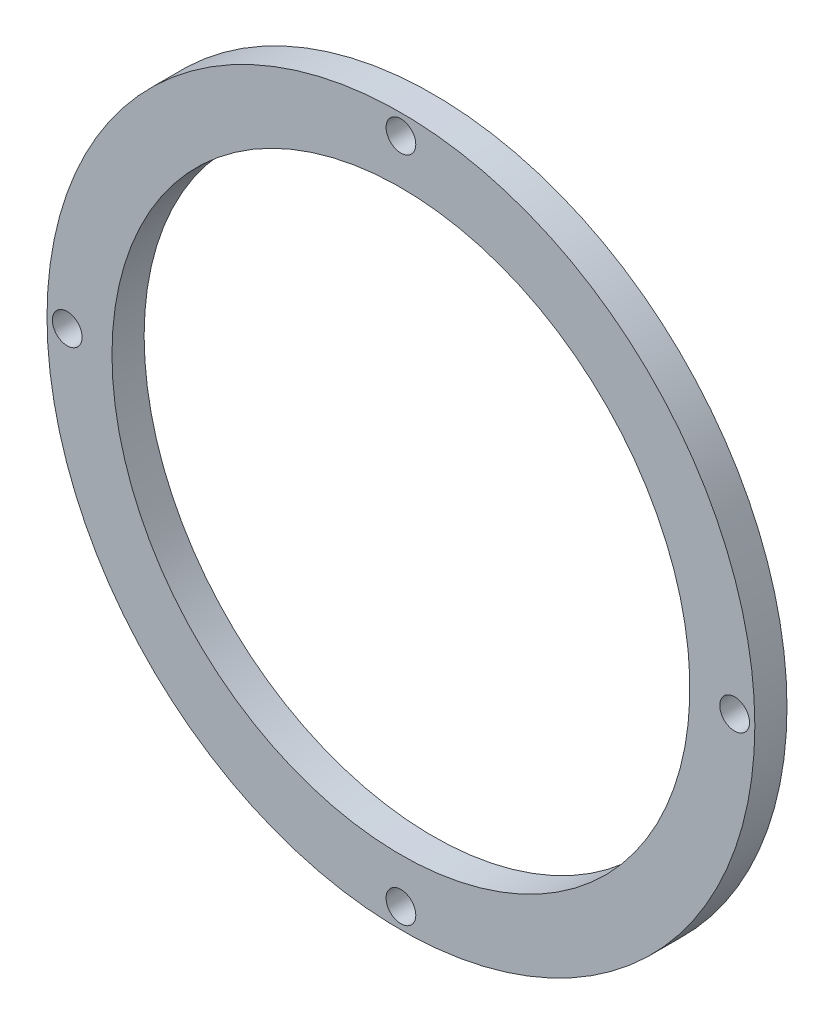
SolidWorks part; units mm, degrees
ref_plane "Front Plane" through (0, 0, 0) normal (0, 0, 1) x (1, 0, 0)
ref_plane "Top Plane" through (0, 0, 0) normal (0, 1, 0) x (1, 0, 0)
ref_plane "Right Plane" through (0, 0, 0) normal (1, 0, 0) x (0, 0, -1)
sketch "Sketch1" plane through (0, 0, 0) normal (0, 0, 1) x (1, 0, 0)
  circle A0 centre (0, 0) radius 35
  circle A1 centre (0, 0) radius 28.575
  dimension "D1" = 57.15
  dimension "D2" = 70
extrude "Boss-Extrude1" add sketch "Sketch1" along normal blind 3.18
sketch "Sketch2" plane through (0, 0, 3.18) normal (0, 0, 1) x (1, 0, 0)
  circle A0 centre (0, 33) radius 1.47
  circle A3 centre (0, 0) radius 35 construction
  dimension "D1" = 2.94
  dimension "D2" = 33
extrude "Cut-Extrude1" cut sketch "Sketch2" against normal blind 3.18
pattern_circular "CirPattern1" count 4 every 90 about axis through (0, 0, 0) along (0, 0, 1) of "Cut-Extrude1"
